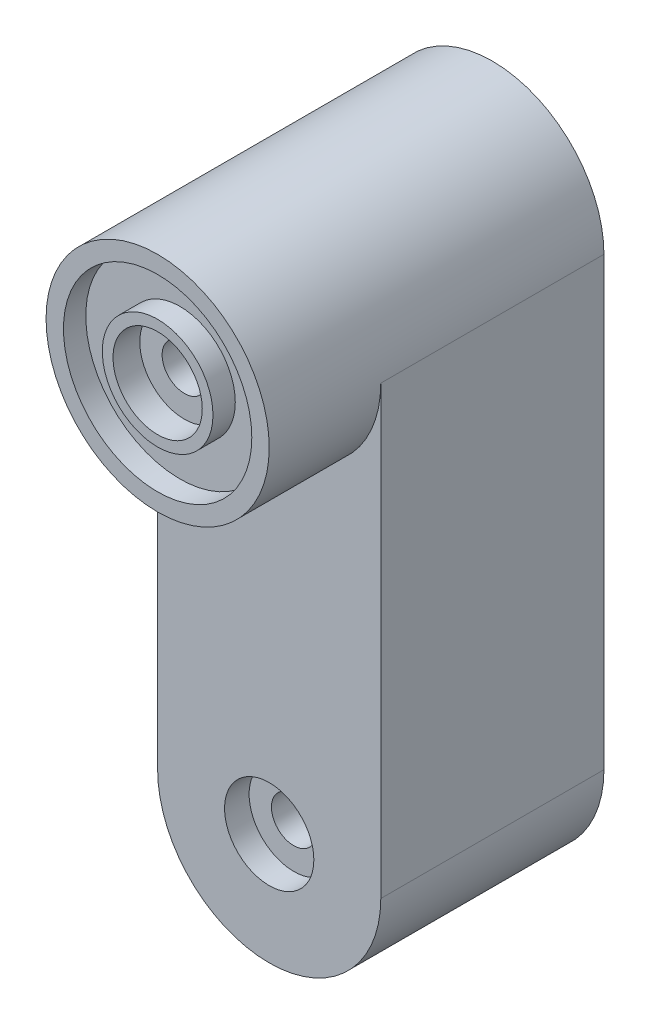
SolidWorks part; units mm, degrees
ref_plane "Ebene vorne" through (0, 0, 0) normal (0, 0, 1) x (1, 0, 0)
ref_plane "Ebene oben" through (0, 0, 0) normal (0, 1, 0) x (1, 0, 0)
ref_plane "Ebene rechts" through (0, 0, 0) normal (1, 0, 0) x (0, 0, -1)
sketch "Skizze4" plane through (0, 0, 0) normal (0, 1, 0) x (1, 0, 0)
  line L1 (-25, -25) -> (25, -25)
  line L2 (-25, -25) -> (-25, 25)
  line L3 (-25, 25) -> (25, 25)
  line L4 (25, -25) -> (25, 25)
  line L5 (-25, -25) -> (25, 25) construction
  line L6 (-25, 25) -> (25, -25) construction
  point P0 (0, 0)
  dimension "D1" = 50
  dimension "D2" = 50
extrude "Aufsatz-Linear austragen1" add sketch "Skizze4" along normal blind 150
sketch "Skizze5" plane through (0, 0, 25) normal (0, 0, 1) x (1, 0, 0)
  line L0 (25, 150) -> (25, 0) construction
  line L1 (-25, 150) -> (25, 150)
  line L2 (-25, 150) -> (-25, 100)
  line L3 (-25, 100) -> (25, 100)
  line L4 (25, 150) -> (25, 100)
  dimension "D1" = 50
extrude "Aufsatz-Linear austragen2" add sketch "Skizze5" along normal blind 25
sketch "Skizze6" plane through (0, 0, 50) normal (0, 0, 1) x (1, 0, 0)
  line L0 (-25, 150) -> (25, 100) construction
  line L1 (25, 100) -> (25, 150) construction
  line L2 (25, 100) -> (25, 150) construction
  line L3 (25, 150) -> (-25, 100) construction
  circle A0 centre (0, 125) radius 5
extrude "Schnitt-Linear austragen1" cut sketch "Skizze6" against normal blind 75
sketch "Skizze8" plane through (0, 0, 25) normal (0, 0, 1) x (1, 0, 0)
  line L0 (-25, 25) -> (-25, 0)
  line L1 (-25, 0) -> (25, 0)
  line L2 (25, 0) -> (25, 25)
  arc A0 (-25, 25) -> (25, 25) centre (0, 25) ccw
  circle A1 centre (0, 25) radius 5
  line M4 (-25, 100) -> (-25, 0)
  line M5 (-25, 0) -> (25, 0)
  line M6 (25, 0) -> (25, 100)
extrude "Schnitt-Linear austragen2" cut sketch "Skizze8" against normal blind 50 contours A0 M4 M5 | A0 L1 M6 | A1
sketch "Skizze9" plane through (0, 0, 50) normal (0, 0, 1) x (1, 0, 0)
  line L0 (-25, 150) -> (-25, 100)
  line L1 (-25, 100) -> (25, 100) construction
  line L2 (-25, 150) -> (-25, 100) construction
  line L3 (-25, 100) -> (25, 100)
  line L4 (25, 100) -> (25, 150)
  line L5 (25, 150) -> (-25, 150)
  circle A0 centre (0, 125) radius 25
  line M3 (-25, 150) -> (-25, 100)
  line M6 (25, 150) -> (-25, 150)
extrude "Schnitt-Linear austragen3" cut sketch "Skizze9" against normal up to surface (75 mm away) contours A0 L5 M3 | A0 L4 M6 up to face at (5, 25, -25)
sketch "Skizze10" plane through (0, 0, 50) normal (0, 0, 1) x (1, 0, 0)
  line L0 (-25, 125) -> (-25, 100)
  line L1 (-25, 100) -> (25, 100)
  line L2 (25, 100) -> (25, 125)
  circle A0 centre (0, 125) radius 25
  line M2 (25, 100) -> (25, 125)
  line M4 (-25, 125) -> (-25, 100)
  line M5 (-25, 100) -> (25, 100)
extrude "Schnitt-Linear austragen4" cut sketch "Skizze10" against normal up to surface (25 mm away) contours A0 M4 M5 | A0 L1 M2 up to face at (5, 25, 25)
sketch "Skizze11" plane through (0, 0, 50) normal (0, 0, 1) x (1, 0, 0)
  circle A0 centre (0, 125) radius 21.1
  circle A1 centre (0, 125) radius 12.4
  dimension "D1" = 24.8
  dimension "D2" = 42.2
extrude "Schnitt-Linear austragen5" cut sketch "Skizze11" against normal blind 5 contours A0 | A1
sketch "Skizze12" plane through (0, 0, -25) normal (0, 0, -1) x (-1, 0, 0)
  circle A0 centre (0, 125) radius 10.2
  circle A1 centre (0, 25) radius 10
extrude "Schnitt-Linear austragen6" cut sketch "Skizze12" against normal blind 5.5
sketch "Skizze13" plane through (0, 0, 50) normal (0, 0, 1) x (1, 0, 0)
  circle A1 centre (0, 125) radius 10
extrude "Schnitt-Linear austragen7" cut sketch "Skizze13" against normal blind 6 contours A1
sketch "Skizze14" plane through (0, 0, 25) normal (0, 0, 1) x (1, 0, 0)
  circle A0 centre (0, 25) radius 10
extrude "Schnitt-Linear austragen8" cut sketch "Skizze14" against normal blind 5.5
